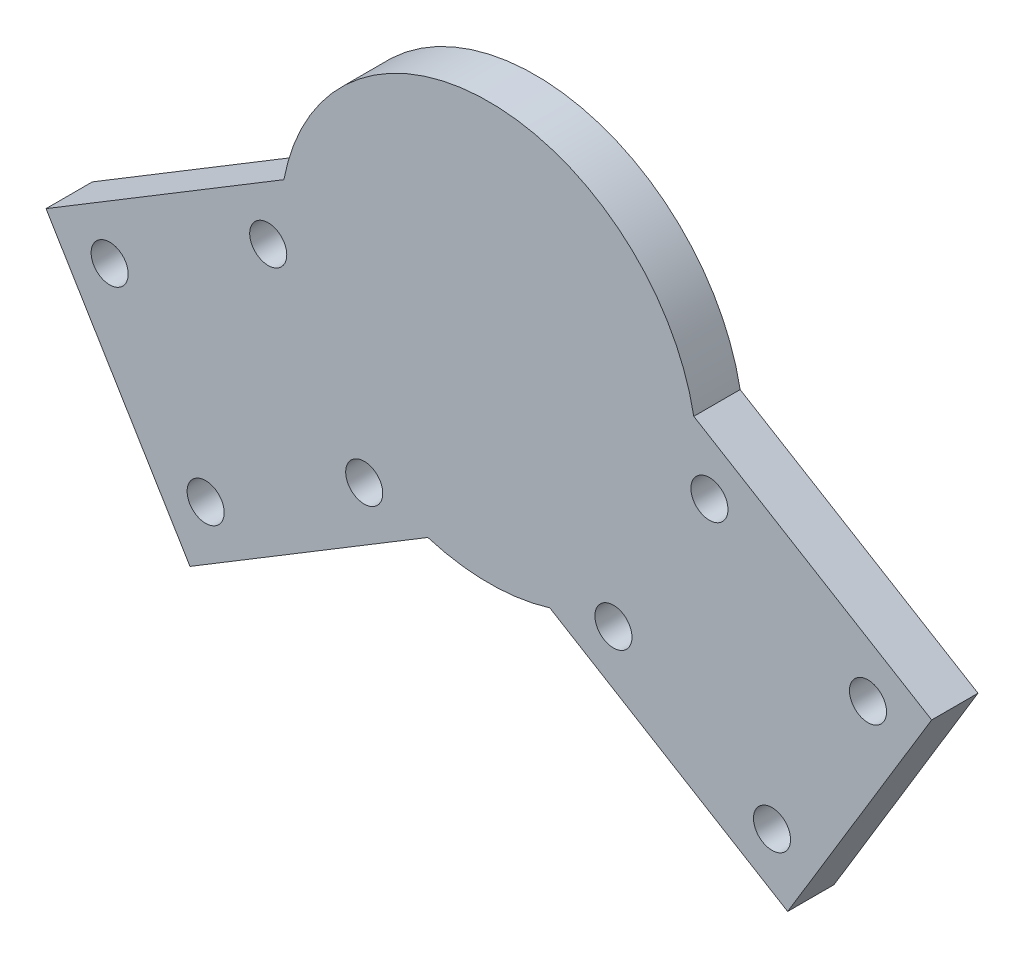
SolidWorks part; units mm, degrees
ref_plane "Front Plane" through (0, 0, 0) normal (0, 0, 1) x (1, 0, 0)
ref_plane "Top Plane" through (0, 0, 0) normal (0, 1, 0) x (1, 0, 0)
ref_plane "Right Plane" through (0, 0, 0) normal (1, 0, 0) x (0, 0, -1)
sketch "Sketch2" plane through (0, 0, 0) normal (0, 0, 1) x (1, 0, 0)
  line L8 (0, 0) -> (0, -22.5) construction
  line L9 (0, 0) -> (6.5784, -21.5169)
  line L10 (0, 0) -> (-6.5784, -21.5169)
  line L11 (6.5784, -21.5169) -> (22.1146, 4.1469)
  line L12 (6.5784, -21.5169) -> (32.2421, -37.053)
  line L13 (22.1146, 4.1469) -> (47.7783, -11.3893)
  line L14 (32.2421, -37.053) -> (47.7783, -11.3893)
  line L15 (-6.5784, -21.5169) -> (-22.1146, 4.1469)
  line L16 (-6.5784, -21.5169) -> (-32.2421, -37.053)
  line L17 (-22.1146, 4.1469) -> (-47.7783, -11.3893)
  line L18 (-32.2421, -37.053) -> (-47.7783, -11.3893)
  circle A0 centre (0, 0) radius 22.5
  dimension "D5" = 45
  dimension "D1" = 17
  dimension "D2" = 17
  dimension "D3" = 30
  dimension "D4" = 30
  dimension "D6" = 30
  dimension "D7" = 30
extrude "Boss-Extrude1" add sketch "Sketch2" along normal blind 5
sketch "Sketch4" plane through (0, 0, 5) normal (0, 0, 1) x (1, 0, 0)
  line L0 (-22.1146, 4.1469) -> (-6.5784, -21.5169)
  line L1 (-22.1146, 4.1469) -> (-47.7783, -11.3893) construction
  line L2 (-6.5784, -21.5169) -> (-32.2421, -37.053) construction
  line L3 (-32.2421, -37.053) -> (-47.7783, -11.3893) construction
  line L4 (6.5784, -21.5169) -> (22.1146, 4.1469)
  line L7 (6.5784, -21.5169) -> (32.2421, -37.053) construction
  line L8 (22.1146, 4.1469) -> (47.7783, -11.3893) construction
  line L9 (32.2421, -37.053) -> (47.7783, -11.3893) construction
  circle A0 centre (-40.9116, -13.0772) radius 2
  circle A1 centre (-23.8025, -2.7198) radius 2
  circle A2 centre (-13.445, -19.8289) radius 2
  circle A3 centre (-30.5542, -30.1864) radius 2
  circle A4 centre (23.8025, -2.7198) radius 2
  circle A6 centre (13.445, -19.8289) radius 2
  circle A7 centre (40.9116, -13.0772) radius 2
  circle A8 centre (30.5542, -30.1864) radius 2
  dimension "D10" = 4
  dimension "D11" = 4
  dimension "D12" = 4
  dimension "D13" = 4
  dimension "D19" = 4
  dimension "D20" = 4
  dimension "D25" = 4
  dimension "D26" = 4
  dimension "D1" = 30
  dimension "D2" = 5
  dimension "D3" = 5
  dimension "D4" = 5
  dimension "D5" = 5
  dimension "D6" = 5
  dimension "D7" = 5
  dimension "D8" = 5
  dimension "D9" = 5
  dimension "D14" = 30
  dimension "D15" = 5
  dimension "D16" = 5
  dimension "D17" = 5
  dimension "D18" = 5
  dimension "D21" = 5
  dimension "D22" = 5
  dimension "D23" = 5
  dimension "D24" = 5
extrude "Cut-Extrude1" cut sketch "Sketch4" against normal blind 10 contours A0 | A1 | A2 | A3 | A6 | A4 | A7 | A8
